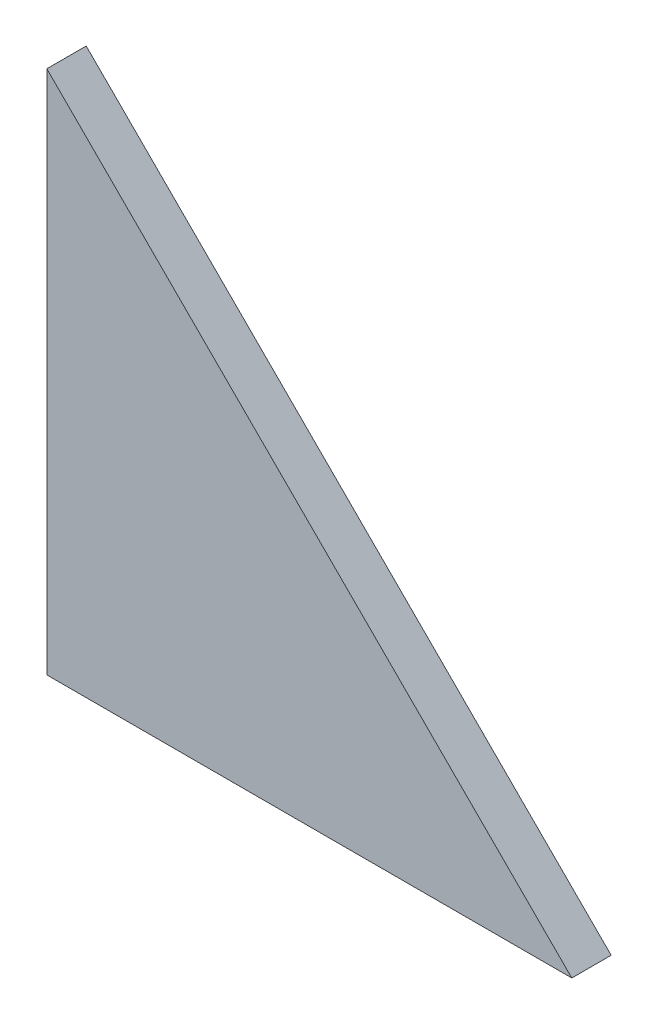
SolidWorks part; units mm, degrees
material "Chapa F.F 1020 - 1,5 mm"
ref_plane "Plano frontal" through (0, 0, 0) normal (0, 0, 1) x (1, 0, 0)
ref_plane "Plano superior" through (0, 0, 0) normal (0, 1, 0) x (1, 0, 0)
ref_plane "Plano direito" through (0, 0, 0) normal (1, 0, 0) x (0, 0, -1)
sketch "Esboço1" plane through (0, 0, 0) normal (0, 0, 1) x (1, 0, 0)
  line L1 (0, 0) -> (20, 0)
  line L2 (0, 0) -> (0, 20)
  line L3 (0, 20) -> (20, 20)
  line L4 (20, 0) -> (20, 20)
  dimension "D1" = 20
  dimension "D2" = 20
extrude "Ressalto-extrusão1" add sketch "Esboço1" along normal blind 1.5
sketch "Esboço2" plane through (0, 0, 1.5) normal (0, 0, 1) x (1, 0, 0)
  line L0 (0, 20) -> (20, 0)
extrude "Corte-extrusão1" cut sketch "Esboço2" against normal through all and the other way through all
